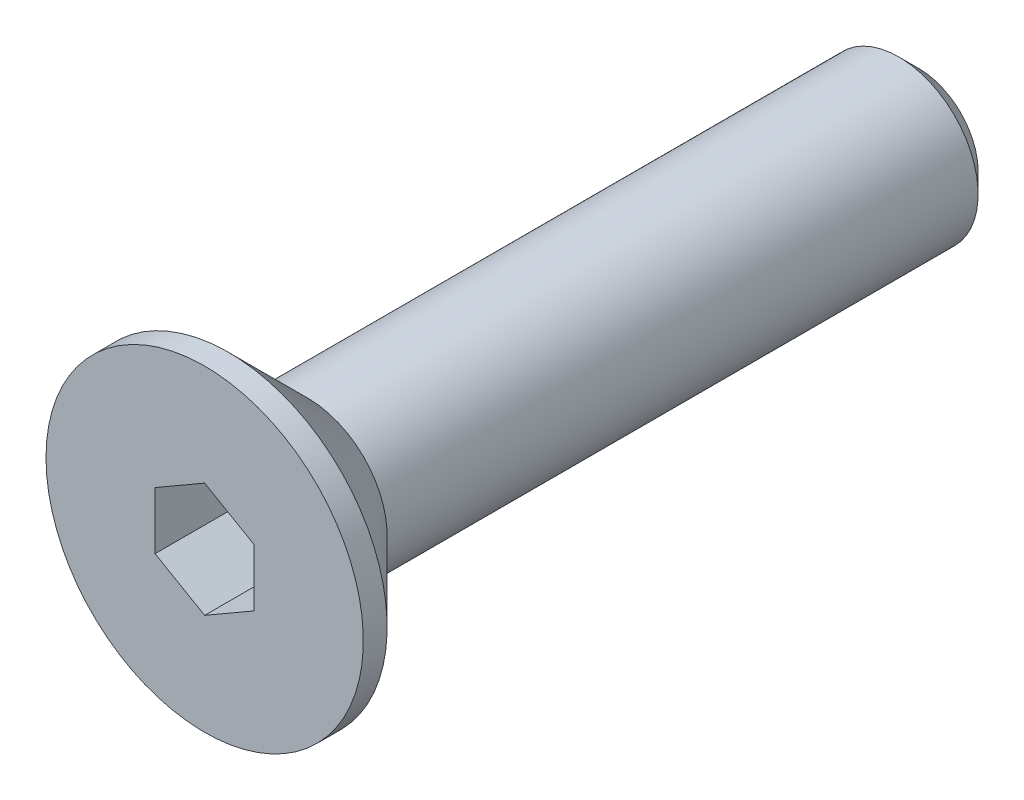
SolidWorks part; units mm, degrees
ref_plane "前视基准面" through (0, 0, 0) normal (0, 0, 1) x (1, 0, 0)
ref_plane "上视基准面" through (0, 0, 0) normal (0, 1, 0) x (1, 0, 0)
ref_plane "右视基准面" through (0, 0, 0) normal (1, 0, 0) x (0, 0, -1)
sketch "草图1" plane through (0, 0, 0) normal (1, 0, 0) x (0, 0, -1)
  line L0 (-9, 0) -> (-9, 4)
  line L1 (-9, 4) -> (-8.4, 4)
  line L2 (-8.4, 4) -> (-6.4, 2)
  line L3 (-6.4, 2) -> (9, 2)
  line L5 (9, 2) -> (9, 0)
  line L6 (9, 0) -> (-9, 0)
  dimension "D1" = 45
  dimension "D2" = 2
  dimension "D3" = 18
  dimension "D4" = 4
  dimension "D5" = 2.6
revolve "旋转1" add sketch "草图1" angle 360 about L6
chamfer "倒角1" distance 0.5 angle 45 1 edges at (-2, 0, -9)
sketch "草图2" plane through (0, 0, 9) normal (0, 0, 1) x (1, 0, 0)
  line L1 (0, 1.4434) -> (-1.25, 0.7217)
  line L2 (-1.25, 0.7217) -> (-1.25, -0.7217)
  line L3 (-1.25, -0.7217) -> (0, -1.4434)
  line L4 (0, -1.4434) -> (1.25, -0.7217)
  line L5 (1.25, -0.7217) -> (1.25, 0.7217)
  line L6 (1.25, 0.7217) -> (0, 1.4434)
  circle A0 centre (0, 0) radius 1.25 construction
  dimension "D1" = 2.5
extrude "切除-拉伸1" cut sketch "草图2" against normal blind 2.5
